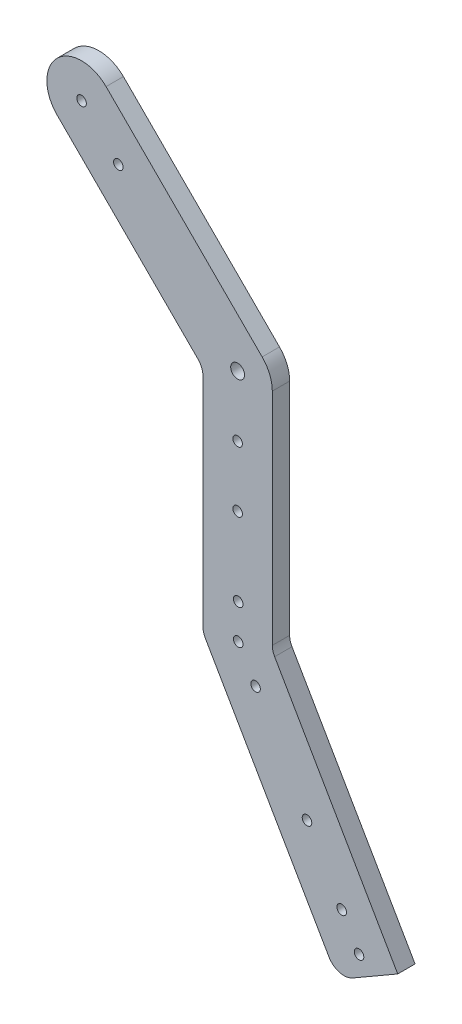
SolidWorks part; units mm, degrees
ref_plane "Front Plane" through (0, 0, 0) normal (0, 0, 1) x (1, 0, 0)
ref_plane "Top Plane" through (0, 0, 0) normal (0, 1, 0) x (1, 0, 0)
ref_plane "Right Plane" through (0, 0, 0) normal (1, 0, 0) x (0, 0, -1)
sketch "Sketch1" plane through (0, 0, 0) normal (0, 0, 1) x (1, 0, 0)
  line L0 (0, 125) -> (0, 250)
  line L1 (20, 130.359) -> (92.3205, 5.0962)
  line L2 (0, 125) -> (75, -4.9038)
  line L3 (20, 130.359) -> (20, 250)
  line L4 (-20, 119.641) -> (57.6795, -14.9038)
  line L5 (-20, 119.641) -> (-20, 250)
  line L6 (-20, 250) -> (20, 250)
  line L7 (92.3205, 5.0962) -> (57.6795, -14.9038)
  dimension "D1" = 125
  dimension "D2" = 150
  dimension "D3" = 30
  dimension "D4" = 20
  dimension "D5" = 20
extrude "Boss-Extrude1" add sketch "Sketch1" along normal blind 10 contours L7 L2 L0 L6 L5 L4 | L7 L1 L3 L6 L0 L2
fillet "Fillet1" radius 10 3 edges at (57.6795, -14.9038, 5) (-20, 119.641, 5) (20, 130.359, 5)
sketch "Sketch2" plane through (0, 0, 10) normal (0, 0, 1) x (1, 0, 0)
  line L0 (0, 250) -> (0, 270)
  line L1 (-20, 250) -> (20, 250) construction
  line L2 (20, 250) -> (20, 260)
  line L3 (-20, 250) -> (-20, 260)
  circle A0 centre (0, 260) radius 4
  circle A1 centre (0, 260) radius 20
  dimension "D2" = 8
  dimension "D3" = 40
  dimension "D1" = 20
extrude "Boss-Extrude2" add sketch "Sketch2" against normal blind 10
sketch "Sketch3" plane through (0, 0, 10) normal (0, 0, 1) x (1, 0, 0)
  circle A0 centre (0, 190) radius 2.75
  circle A1 centre (0, 225) radius 2.75
  dimension "D1" = 5.5
  dimension "D2" = 5.5
extrude "Cut-Extrude1" cut sketch "Sketch3" against normal through all
sketch "Sketch5" plane through (0, 0, 10) normal (0, 0, 1) x (1, 0, 0)
  circle A0 centre (60, 21.077) radius 2.75
  circle A1 centre (70, 3.7564) radius 2.75
extrude "Cut-Extrude2" cut sketch "Sketch5" against normal through all both and the other way through all
sketch "Sketch7" plane through (0, 0, 10) normal (0, 0, 1) x (1, 0, 0)
  line L0 (0, 260) -> (-120, 380)
  line L1 (0, 260) -> (-20, 260) construction
  line L4 (14.1421, 274.1421) -> (-105.8579, 394.1421)
  line L5 (-14.1421, 245.8579) -> (-134.1421, 365.8579)
  circle A0 centre (0, 260) radius 20
  circle A1 centre (-120, 380) radius 20
  dimension "D1" = 45
  dimension "D2" = 20
  dimension "D3" = 20
extrude "Boss-Extrude3" add sketch "Sketch7" against normal blind 10
fillet "Fillet2" radius 10 1 edges at (-20, 251.7157, 5)
sketch "Sketch8" plane through (0, 0, 10) normal (0, 0, 1) x (1, 0, 0)
  line L0 (-45.8579, 334.1421) -> (-105.8579, 394.1421)
  line L1 (14.1421, 274.1421) -> (-105.8579, 394.1421) construction
  line L2 (-75.8579, 364.1421) -> (-104.1421, 335.8579)
  line L3 (-22.9289, 254.6447) -> (-134.1421, 365.8579) construction
  line L11 (-134.1421, 365.8579) -> (-22.9289, 254.6447)
  line L12 (-20, 247.5736) -> (-20, 122.3205)
  line L13 (-18.6603, 117.3205) -> (52.6795, -6.2436)
  line L14 (66.3397, -9.9038) -> (92.3205, 5.0962)
  line L15 (92.3205, 5.0962) -> (21.3397, 128.0385)
  line L16 (20, 133.0385) -> (20, 260)
  line L17 (14.1421, 274.1421) -> (-105.8579, 394.1421)
  line L18 (-134.1421, 365.8579) -> (-104.1421, 335.8579)
  line L19 (-20, 247.5736) -> (-20, 122.3205)
  line L20 (-18.6603, 117.3205) -> (52.6795, -6.2436)
  line L21 (66.3397, -9.9038) -> (92.3205, 5.0962)
  line L22 (92.3205, 5.0962) -> (21.3397, 128.0385)
  line L23 (20, 133.0385) -> (20, 260)
  line L24 (-45.8579, 334.1421) -> (-105.8579, 394.1421)
  circle A0 centre (-90, 350) radius 20
  arc A7 (-20, 247.5736) -> (-22.9289, 254.6447) centre (-30, 247.5736) ccw
  arc A8 (-20, 122.3205) -> (-18.6603, 117.3205) centre (-10, 122.3205) ccw
  arc A9 (52.6795, -6.2436) -> (66.3397, -9.9038) centre (61.3397, -1.2436) ccw
  arc A10 (20, 133.0385) -> (21.3397, 128.0385) centre (30, 133.0385) ccw
  arc A11 (20, 260) -> (14.1421, 274.1421) centre (0, 260) ccw
  arc A12 (-105.8579, 394.1421) -> (-134.1421, 365.8579) centre (-120, 380) ccw
  arc A13 (-20, 247.5736) -> (-22.9289, 254.6447) centre (-30, 247.5736) ccw
  arc A14 (-20, 122.3205) -> (-18.6603, 117.3205) centre (-10, 122.3205) ccw
  arc A15 (52.6795, -6.2436) -> (66.3397, -9.9038) centre (61.3397, -1.2436) ccw
  arc A16 (20, 133.0385) -> (21.3397, 128.0385) centre (30, 133.0385) ccw
  arc A17 (20, 260) -> (14.1421, 274.1421) centre (0, 260) ccw
  arc A18 (-105.8579, 394.1421) -> (-134.1421, 365.8579) centre (-120, 380) ccw
  line M14 (-134.1421, 365.8579) -> (-22.9289, 254.6447)
  arc M26 (-105.8579, 394.1421) -> (-134.1421, 365.8579) centre (-120, 380) ccw
  dimension "D1" = 0
extrude "Cut-Extrude3" cut sketch "Sketch8" against normal blind 10 contours A0 L0 M26 M14
sketch "Sketch9" plane through (0, 0, 10) normal (0, 0, 1) x (1, 0, 0)
  line L0 (-90, 350) -> (-68.7868, 328.7868)
  line L1 (-79.3934, 339.3934) -> (-76.6819, 342.1049)
  line L2 (-79.3934, 339.3934) -> (-93.8184, 324.9684)
  circle A0 centre (-90, 350) radius 2.75
  circle A1 centre (-68.7868, 328.7868) radius 2.75
  circle A2 centre (-90, 350) radius 15
  circle A3 centre (-68.7868, 328.7868) radius 15
  dimension "D1" = 5.5
  dimension "D2" = 30
  dimension "D3" = 20.4
extrude "Cut-Extrude4" cut sketch "Sketch9" against normal through all
sketch "Sketch10" plane through (0, 0, 10) normal (0, 0, 1) x (1, 0, 0)
  line L0 (60, 21.077) -> (40, 55.718)
  line L1 (-18.6603, 117.3205) -> (52.6795, -6.2436) construction
  circle A0 centre (40, 55.718) radius 2.75
  dimension "D2" = 5.5
  dimension "D1" = 40
extrude "Cut-Extrude5" cut sketch "Sketch10" against normal through all
sketch "Sketch11" plane through (0, 0, 10) normal (0, 0, 1) x (1, 0, 0)
  circle A0 centre (0.3407, 145.0913) radius 2.75
  circle A1 centre (0.3407, 125.0913) radius 2.75
  circle A2 centre (10.3407, 107.7708) radius 2.75
extrude "Cut-Extrude6" cut sketch "Sketch11" against normal through all both and the other way through all
